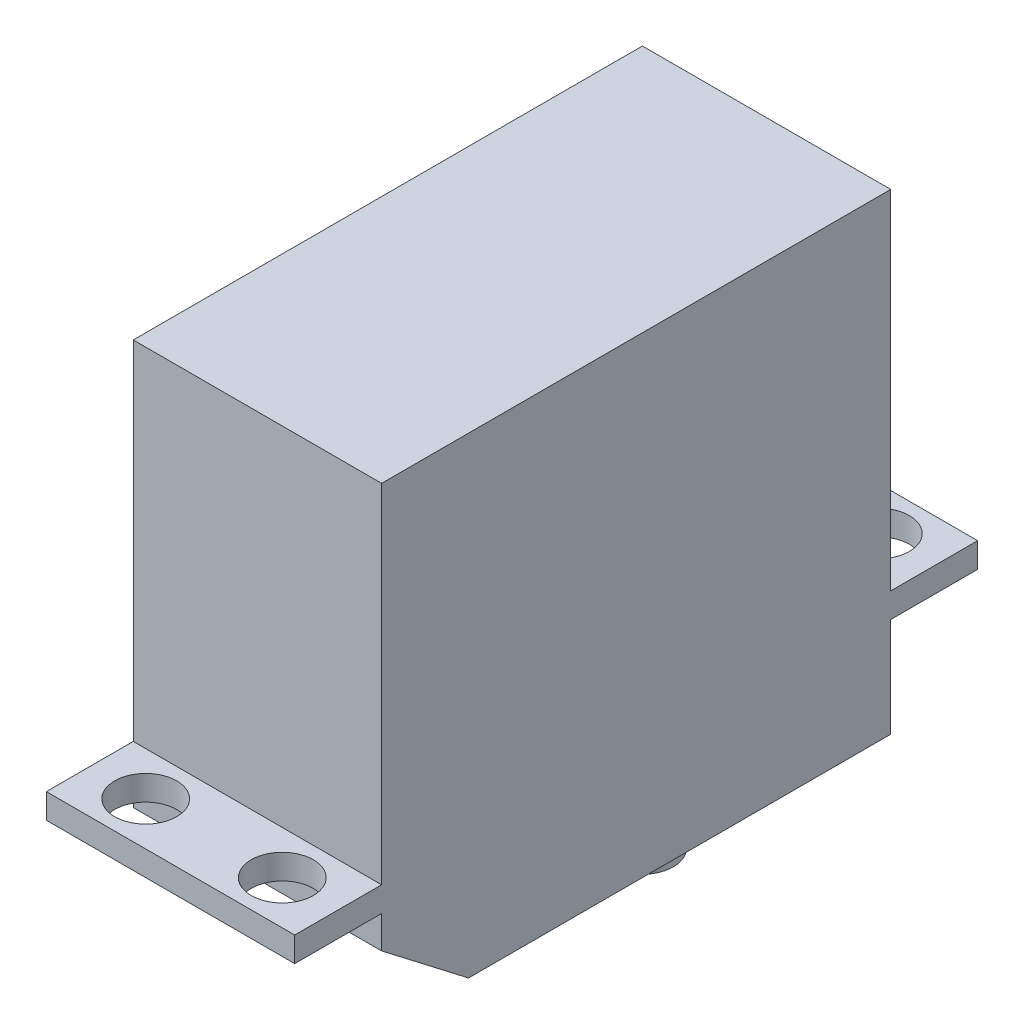
SolidWorks part; units mm, degrees
ref_plane "Alzado" through (0, 0, 0) normal (0, 0, 1) x (1, 0, 0)
ref_plane "Planta" through (0, 0, 0) normal (0, 1, 0) x (1, 0, 0)
ref_plane "Vista lateral" through (0, 0, 0) normal (1, 0, 0) x (0, 0, -1)
sketch "Croquis1" plane through (0, 0, 0) normal (1, 0, 0) x (0, 0, -1)
  line L0 (41, 10) -> (48, 10)
  line L1 (7, 0) -> (41, 0)
  line L2 (0, 5.3878) -> (0, 8)
  line L3 (0, 38) -> (41, 38)
  line L4 (41, 0) -> (41, 8)
  line L5 (-7, 8) -> (0, 8)
  line L6 (-7, 8) -> (-7, 10)
  line L7 (-7, 10) -> (0, 10)
  line L8 (48, 8) -> (48, 10)
  line L9 (41, 8) -> (48, 8)
  line L10 (41, 10) -> (41, 38)
  line L11 (0, 10) -> (0, 38)
  line L12 (7, 0) -> (0, 5.3878)
  dimension "D1" = 28
  dimension "D2" = 2
  dimension "D3" = 7
  dimension "D4" = 7
  dimension "D5" = 41
  dimension "D6" = 8
  dimension "D7" = 7
extrude "Saliente-Extruir1" add sketch "Croquis1" along normal blind 20
sketch "Croquis2" plane through (0, 0, 0) normal (0, -1, 0) x (1, 0, 0)
  line L0 (10, -41) -> (10, -24.5561) construction
  line L1 (20, -41) -> (0, -41) construction
  line L2 (20, -41) -> (0, -41) construction
  circle A0 centre (10, -31) radius 2.5
  dimension "D1" = 5
  dimension "D2" = 10
extrude "Saliente-Extruir2" add sketch "Croquis2" along normal blind 8
sketch "Croquis3" plane through (0, 8, 0) normal (0, -1, 0) x (1, 0, 0)
  line L0 (10, 7) -> (10, -48) construction
  line L1 (20, 7) -> (0, 7) construction
  line L2 (20, -48) -> (0, -48) construction
  line L3 (10, -20.5) -> (33.0871, -20.5) construction
  line L4 (0, 7) -> (0, 0) construction
  circle A0 centre (4.5, 3.5) radius 2.5
  circle A1 centre (15.5, 3.5) radius 2.5
  circle A2 centre (15.5, -44.5) radius 2.5
  circle A3 centre (4.5, -44.5) radius 2.5
  dimension "D1" = 5
  dimension "D2" = 3.5
  dimension "D3" = 4.5
extrude "Cortar-Extruir1" cut sketch "Croquis3" against normal blind 10
